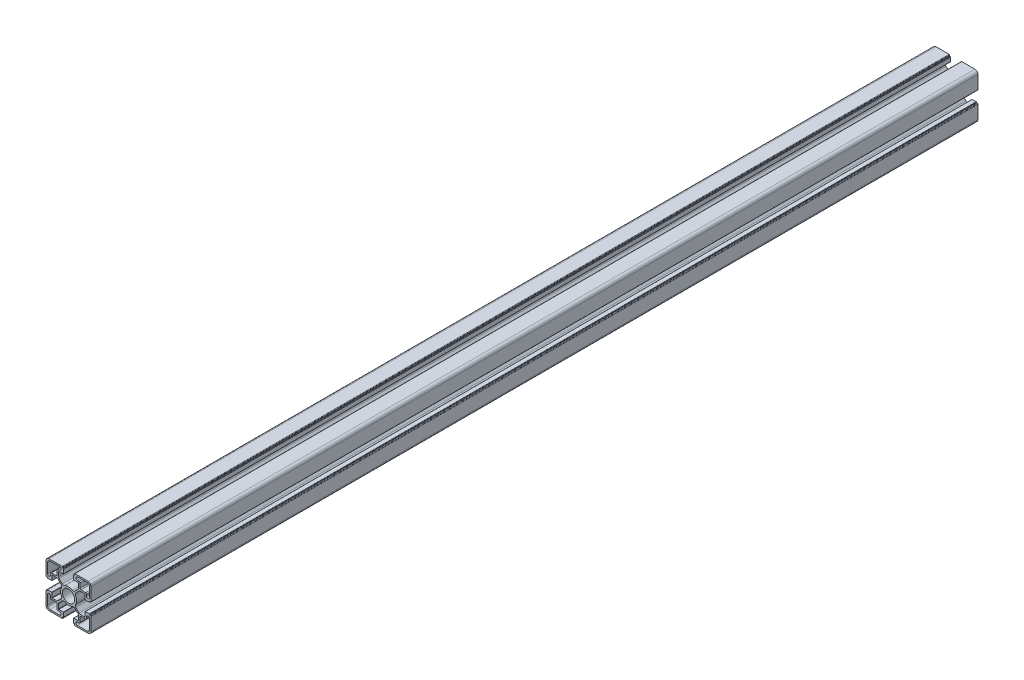
SolidWorks part; units mm, degrees
material "6061 Alloy"
ref_plane "Front Plane" through (0, 0, 0) normal (0, 0, 1) x (1, 0, 0)
ref_plane "Top Plane" through (0, 0, 0) normal (0, 1, 0) x (1, 0, 0)
ref_plane "Right Plane" through (0, 0, 0) normal (1, 0, 0) x (0, 0, -1)
sketch "Sketch1" plane through (0, 0, 0) normal (0, 0, 1) x (1, 0, 0)
  line L3 (-22.5, 19.5) -> (-22.5, 6.3)
  line L4 (-20.7, 5) -> (-16.7, 5)
  line L5 (-16.5, 5.2) -> (-16.5, 9.8)
  line L6 (-16.3, 10) -> (-11.8642, 10)
  line L7 (-10.4924, 9.4318) -> (-7.2967, 6.236)
  line L8 (-21, 18.5) -> (-21, 9)
  line L9 (-16.5, 5) -> (-16.5, 10) construction
  line L10 (-18, 9) -> (-18, 10.5)
  line L11 (-17, 11.5) -> (-12.5, 11.5)
  line L12 (-22, 5.8) -> (-21.3, 5.8)
  line L13 (-21, 5.5) -> (-21, 5.3)
  line L14 (-21, 22.5) -> (-21, 6.5) construction
  line L15 (-18, 11.5) -> (-10.4393, 11.5) construction
  line L16 (-10.4393, 11.5) -> (-5.1016, 6.1623) construction
  line L17 (-18, 6.5) -> (-18, 11.5) construction
  line L18 (-22.5, 22.5) -> (-22.5, 5) construction
  line L19 (-22.5, 5) -> (-16.5, 5) construction
  line L20 (-21, 6.5) -> (-18, 6.5) construction
  line L21 (-16.5, 10) -> (-11.0607, 10) construction
  line L22 (-11.0607, 10) -> (-6.1623, 5.1016) construction
  line L23 (-5.5, 21) -> (-5.3, 21)
  line L24 (-5.8, 22) -> (-5.8, 21.3)
  line L25 (-11.5, 17) -> (-11.5, 12.5)
  line L26 (-9, 18) -> (-10.5, 18)
  line L27 (-18.5, 21) -> (-9, 21)
  line L28 (-9.4318, 10.4924) -> (-6.236, 7.2967)
  line L29 (-10, 16.3) -> (-10, 11.8642)
  line L30 (-5.2, 16.5) -> (-9.8, 16.5)
  line L31 (-5, 20.7) -> (-5, 16.7)
  line L32 (-19.5, 22.5) -> (-6.3, 22.5)
  line L33 (19.5, 22.5) -> (6.3, 22.5)
  line L34 (5, 20.7) -> (5, 16.7)
  line L35 (5.2, 16.5) -> (9.8, 16.5)
  line L36 (10, 16.3) -> (10, 11.8642)
  line L37 (9.4318, 10.4924) -> (6.236, 7.2967)
  line L38 (18.5, 21) -> (9, 21)
  line L39 (9, 18) -> (10.5, 18)
  line L40 (11.5, 17) -> (11.5, 12.5)
  line L41 (5.8, 22) -> (5.8, 21.3)
  line L42 (5.5, 21) -> (5.3, 21)
  line L43 (21, 5.5) -> (21, 5.3)
  line L44 (22, 5.8) -> (21.3, 5.8)
  line L45 (17, 11.5) -> (12.5, 11.5)
  line L46 (18, 9) -> (18, 10.5)
  line L47 (21, 18.5) -> (21, 9)
  line L48 (10.4924, 9.4318) -> (7.2967, 6.236)
  line L49 (16.3, 10) -> (11.8642, 10)
  line L50 (16.5, 5.2) -> (16.5, 9.8)
  line L51 (20.7, 5) -> (16.7, 5)
  line L52 (22.5, 19.5) -> (22.5, 6.3)
  line L53 (22.5, -19.5) -> (22.5, -6.3)
  line L54 (20.7, -5) -> (16.7, -5)
  line L55 (16.5, -5.2) -> (16.5, -9.8)
  line L56 (16.3, -10) -> (11.8642, -10)
  line L57 (10.4924, -9.4318) -> (7.2967, -6.236)
  line L58 (21, -18.5) -> (21, -9)
  line L59 (18, -9) -> (18, -10.5)
  line L60 (17, -11.5) -> (12.5, -11.5)
  line L61 (22, -5.8) -> (21.3, -5.8)
  line L62 (21, -5.5) -> (21, -5.3)
  line L63 (5.5, -21) -> (5.3, -21)
  line L64 (5.8, -22) -> (5.8, -21.3)
  line L65 (11.5, -17) -> (11.5, -12.5)
  line L66 (9, -18) -> (10.5, -18)
  line L67 (18.5, -21) -> (9, -21)
  line L68 (9.4318, -10.4924) -> (6.236, -7.2967)
  line L69 (10, -16.3) -> (10, -11.8642)
  line L70 (5.2, -16.5) -> (9.8, -16.5)
  line L71 (5, -20.7) -> (5, -16.7)
  line L72 (19.5, -22.5) -> (6.3, -22.5)
  line L73 (-19.5, -22.5) -> (-6.3, -22.5)
  line L74 (-5, -20.7) -> (-5, -16.7)
  line L75 (-5.2, -16.5) -> (-9.8, -16.5)
  line L76 (-10, -16.3) -> (-10, -11.8642)
  line L77 (-9.4318, -10.4924) -> (-6.236, -7.2967)
  line L78 (-18.5, -21) -> (-9, -21)
  line L79 (-9, -18) -> (-10.5, -18)
  line L80 (-11.5, -17) -> (-11.5, -12.5)
  line L81 (-5.8, -22) -> (-5.8, -21.3)
  line L82 (-5.5, -21) -> (-5.3, -21)
  line L83 (-21, -5.5) -> (-21, -5.3)
  line L84 (-22, -5.8) -> (-21.3, -5.8)
  line L85 (-17, -11.5) -> (-12.5, -11.5)
  line L86 (-18, -9) -> (-18, -10.5)
  line L87 (-21, -18.5) -> (-21, -9)
  line L88 (-10.4924, -9.4318) -> (-7.2967, -6.236)
  line L89 (-16.3, -10) -> (-11.8642, -10)
  line L90 (-16.5, -5.2) -> (-16.5, -9.8)
  line L91 (-20.7, -5) -> (-16.7, -5)
  line L92 (-22.5, -19.5) -> (-22.5, -6.3)
  arc A0 (0, 6.1) -> (-6.1, 0) centre (0, 0) ccw
  arc A1 (-6.9766, 3.9149) -> (-8, 0) centre (0, 0) ccw
  arc A2 (-21, 9) -> (-18, 9) centre (-19.5, 9) ccw
  arc A3 (-22, 5.8) -> (-22.5, 6.3) centre (-22, 6.3) cw
  arc A4 (-21, 5.3) -> (-20.7, 5) centre (-20.7, 5.3) ccw
  arc A5 (-21.3, 5.8) -> (-21, 5.5) centre (-21.3, 5.5) cw
  arc A6 (-16.7, 5) -> (-16.5, 5.2) centre (-16.7, 5.2) ccw
  arc A7 (-16.5, 9.8) -> (-16.3, 10) centre (-16.3, 9.8) cw
  arc A8 (-7.2967, 6.236) -> (-6.9766, 3.9149) centre (-8.6685, 4.8643) cw
  arc A9 (-11.8642, 10) -> (-10.4924, 9.4318) centre (-11.8642, 8.06) cw
  arc A10 (-18, 10.5) -> (-17, 11.5) centre (-17, 10.5) cw
  arc A11 (-10.5, 18) -> (-11.5, 17) centre (-10.5, 17) ccw
  arc A12 (-10, 11.8642) -> (-9.4318, 10.4924) centre (-8.06, 11.8642) ccw
  arc A13 (-6.236, 7.2967) -> (-3.9149, 6.9766) centre (-4.8643, 8.6685) ccw
  arc A14 (-9.8, 16.5) -> (-10, 16.3) centre (-9.8, 16.3) ccw
  arc A15 (-5, 16.7) -> (-5.2, 16.5) centre (-5.2, 16.7) cw
  arc A16 (-5.8, 21.3) -> (-5.5, 21) centre (-5.5, 21.3) ccw
  arc A17 (-5.3, 21) -> (-5, 20.7) centre (-5.3, 20.7) cw
  arc A18 (-5.8, 22) -> (-6.3, 22.5) centre (-6.3, 22) ccw
  arc A19 (-9, 21) -> (-9, 18) centre (-9, 19.5) cw
  arc A20 (-3.9149, 6.9766) -> (0, 8) centre (0, 0) cw
  arc A21 (-21, 18.5) -> (-18.5, 21) centre (-18.5, 18.5) cw
  arc A22 (-22.5, 19.5) -> (-19.5, 22.5) centre (-19.5, 19.5) cw
  arc A23 (-12.5, 11.5) -> (-11.5, 12.5) centre (-12.5, 12.5) ccw
  arc A24 (6.1, 0) -> (0, 6.1) centre (0, 0) ccw
  arc A25 (3.9149, 6.9766) -> (0, 8) centre (0, 0) ccw
  arc A26 (9, 21) -> (9, 18) centre (9, 19.5) ccw
  arc A27 (5.8, 22) -> (6.3, 22.5) centre (6.3, 22) cw
  arc A28 (5.3, 21) -> (5, 20.7) centre (5.3, 20.7) ccw
  arc A29 (5.8, 21.3) -> (5.5, 21) centre (5.5, 21.3) cw
  arc A30 (5, 16.7) -> (5.2, 16.5) centre (5.2, 16.7) ccw
  arc A31 (9.8, 16.5) -> (10, 16.3) centre (9.8, 16.3) cw
  arc A32 (6.236, 7.2967) -> (3.9149, 6.9766) centre (4.8643, 8.6685) cw
  arc A33 (10, 11.8642) -> (9.4318, 10.4924) centre (8.06, 11.8642) cw
  arc A34 (10.5, 18) -> (11.5, 17) centre (10.5, 17) cw
  arc A35 (18, 10.5) -> (17, 11.5) centre (17, 10.5) ccw
  arc A36 (11.8642, 10) -> (10.4924, 9.4318) centre (11.8642, 8.06) ccw
  arc A37 (7.2967, 6.236) -> (6.9766, 3.9149) centre (8.6685, 4.8643) ccw
  arc A38 (16.5, 9.8) -> (16.3, 10) centre (16.3, 9.8) ccw
  arc A39 (16.7, 5) -> (16.5, 5.2) centre (16.7, 5.2) cw
  arc A40 (21.3, 5.8) -> (21, 5.5) centre (21.3, 5.5) ccw
  arc A41 (21, 5.3) -> (20.7, 5) centre (20.7, 5.3) cw
  arc A42 (22, 5.8) -> (22.5, 6.3) centre (22, 6.3) ccw
  arc A43 (21, 9) -> (18, 9) centre (19.5, 9) cw
  arc A44 (6.9766, 3.9149) -> (8, 0) centre (0, 0) cw
  arc A45 (18.5, 21) -> (21, 18.5) centre (18.5, 18.5) cw
  arc A46 (19.5, 22.5) -> (22.5, 19.5) centre (19.5, 19.5) cw
  arc A47 (11.5, 12.5) -> (12.5, 11.5) centre (12.5, 12.5) ccw
  arc A48 (0, -6.1) -> (6.1, 0) centre (0, 0) ccw
  arc A49 (6.9766, -3.9149) -> (8, 0) centre (0, 0) ccw
  arc A50 (21, -9) -> (18, -9) centre (19.5, -9) ccw
  arc A51 (22, -5.8) -> (22.5, -6.3) centre (22, -6.3) cw
  arc A52 (21, -5.3) -> (20.7, -5) centre (20.7, -5.3) ccw
  arc A53 (21.3, -5.8) -> (21, -5.5) centre (21.3, -5.5) cw
  arc A54 (16.7, -5) -> (16.5, -5.2) centre (16.7, -5.2) ccw
  arc A55 (16.5, -9.8) -> (16.3, -10) centre (16.3, -9.8) cw
  arc A56 (7.2967, -6.236) -> (6.9766, -3.9149) centre (8.6685, -4.8643) cw
  arc A57 (11.8642, -10) -> (10.4924, -9.4318) centre (11.8642, -8.06) cw
  arc A58 (18, -10.5) -> (17, -11.5) centre (17, -10.5) cw
  arc A59 (10.5, -18) -> (11.5, -17) centre (10.5, -17) ccw
  arc A60 (10, -11.8642) -> (9.4318, -10.4924) centre (8.06, -11.8642) ccw
  arc A61 (6.236, -7.2967) -> (3.9149, -6.9766) centre (4.8643, -8.6685) ccw
  arc A62 (9.8, -16.5) -> (10, -16.3) centre (9.8, -16.3) ccw
  arc A63 (5, -16.7) -> (5.2, -16.5) centre (5.2, -16.7) cw
  arc A64 (5.8, -21.3) -> (5.5, -21) centre (5.5, -21.3) ccw
  arc A65 (5.3, -21) -> (5, -20.7) centre (5.3, -20.7) cw
  arc A66 (5.8, -22) -> (6.3, -22.5) centre (6.3, -22) ccw
  arc A67 (9, -21) -> (9, -18) centre (9, -19.5) cw
  arc A68 (3.9149, -6.9766) -> (0, -8) centre (0, 0) cw
  arc A69 (21, -18.5) -> (18.5, -21) centre (18.5, -18.5) cw
  arc A70 (22.5, -19.5) -> (19.5, -22.5) centre (19.5, -19.5) cw
  arc A71 (12.5, -11.5) -> (11.5, -12.5) centre (12.5, -12.5) ccw
  arc A72 (-6.1, 0) -> (0, -6.1) centre (0, 0) ccw
  arc A73 (-3.9149, -6.9766) -> (0, -8) centre (0, 0) ccw
  arc A74 (-9, -21) -> (-9, -18) centre (-9, -19.5) ccw
  arc A75 (-5.8, -22) -> (-6.3, -22.5) centre (-6.3, -22) cw
  arc A76 (-5.3, -21) -> (-5, -20.7) centre (-5.3, -20.7) ccw
  arc A77 (-5.8, -21.3) -> (-5.5, -21) centre (-5.5, -21.3) cw
  arc A78 (-5, -16.7) -> (-5.2, -16.5) centre (-5.2, -16.7) ccw
  arc A79 (-9.8, -16.5) -> (-10, -16.3) centre (-9.8, -16.3) cw
  arc A80 (-6.236, -7.2967) -> (-3.9149, -6.9766) centre (-4.8643, -8.6685) cw
  arc A81 (-10, -11.8642) -> (-9.4318, -10.4924) centre (-8.06, -11.8642) cw
  arc A82 (-10.5, -18) -> (-11.5, -17) centre (-10.5, -17) cw
  arc A83 (-18, -10.5) -> (-17, -11.5) centre (-17, -10.5) ccw
  arc A84 (-11.8642, -10) -> (-10.4924, -9.4318) centre (-11.8642, -8.06) ccw
  arc A85 (-7.2967, -6.236) -> (-6.9766, -3.9149) centre (-8.6685, -4.8643) ccw
  arc A86 (-16.5, -9.8) -> (-16.3, -10) centre (-16.3, -9.8) ccw
  arc A87 (-16.7, -5) -> (-16.5, -5.2) centre (-16.7, -5.2) cw
  arc A88 (-21.3, -5.8) -> (-21, -5.5) centre (-21.3, -5.5) ccw
  arc A89 (-21, -5.3) -> (-20.7, -5) centre (-20.7, -5.3) cw
  arc A90 (-22, -5.8) -> (-22.5, -6.3) centre (-22, -6.3) ccw
  arc A91 (-21, -9) -> (-18, -9) centre (-19.5, -9) cw
  arc A92 (-6.9766, -3.9149) -> (-8, 0) centre (0, 0) cw
  arc A93 (-18.5, -21) -> (-21, -18.5) centre (-18.5, -18.5) cw
  arc A94 (-19.5, -22.5) -> (-22.5, -19.5) centre (-19.5, -19.5) cw
  arc A95 (-11.5, -12.5) -> (-12.5, -11.5) centre (-12.5, -12.5) ccw
  point P24 (-5.8, 21)
  point P32 (-22.5, 5.8)
  point P35 (-21, 5)
  point P38 (-21, 5.8)
  point P83 (-5, 21)
  point P84 (-5.8, 22.5)
  point P87 (-21, 21)
  point P93 (-11.5, 11.5)
  point P102 (21, 5.8)
  point P158 (21, 5)
  point P159 (22.5, 5.8)
  point P172 (5.8, -21)
  point P228 (5, -21)
  point P229 (5.8, -22.5)
  point P242 (-21, -5.8)
  point P298 (-21, -5)
  point P299 (-22.5, -5.8)
  dimension "D11" = 0.5
  dimension "D12" = 0.3
  dimension "D13" = 0.2
  dimension "D14" = 0.2
  dimension "D6" = 1.94
  dimension "D15" = 1
  dimension "D16" = 2.5
  dimension "D4" = 3
  dimension "D17" = 1
  dimension "D5" = 0.8
  dimension "D7" = 1.5
  dimension "D9" = 1.5
  dimension "D10" = 4
  dimension "D18" = 4
extrude "Boss-Extrude4" add sketch "Sketch1" along normal blind 885.8241
scale "Scale1" scale about centroid uniform scaling yes scale factor 0.564444
